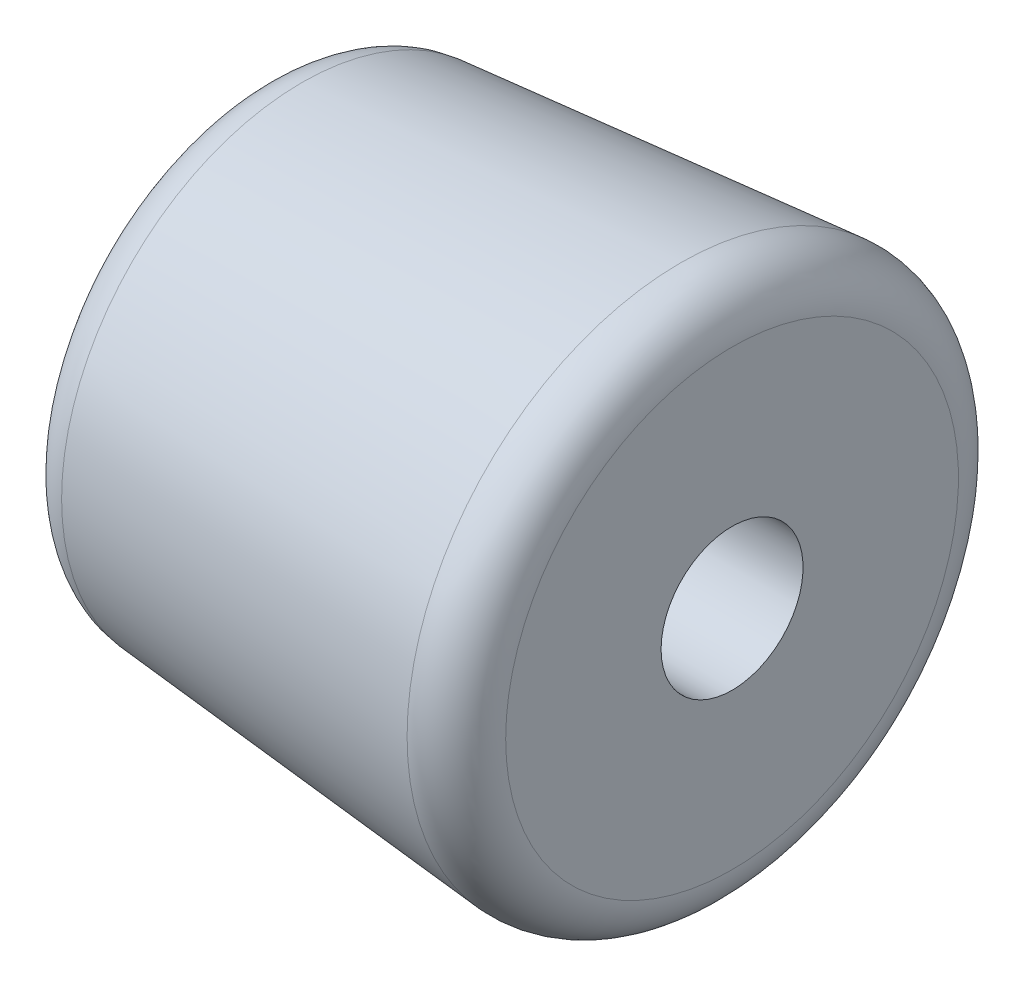
SolidWorks part; units mm, degrees
ref_plane "Plano frontal" through (0, 0, 0) normal (0, 0, 1) x (1, 0, 0)
ref_plane "Plano superior" through (0, 0, 0) normal (0, 1, 0) x (1, 0, 0)
ref_plane "Plano direito" through (0, 0, 0) normal (1, 0, 0) x (0, 0, -1)
sketch "Esboço1" plane through (0, 0, 0) normal (0, 0, 1) x (1, 0, 0)
  line L0 (0, 0) -> (79.197, 0) construction
  line L1 (0, 3) -> (0, 10)
  line L2 (0, 10) -> (20, 11.7498)
  line L3 (20, 11.7498) -> (20, 3)
  line L4 (20, 3) -> (0, 3)
  point P8 (0, 6.5)
  dimension "D1" = 5
  dimension "D2" = 6
  dimension "D3" = 20
  dimension "D4" = 20
revolve "Revolução1" add sketch "Esboço1" angle 360 about L0
fillet "Filete1" radius 2 2 edges at (0, 0, 10) (20, 0, 11.7498)
